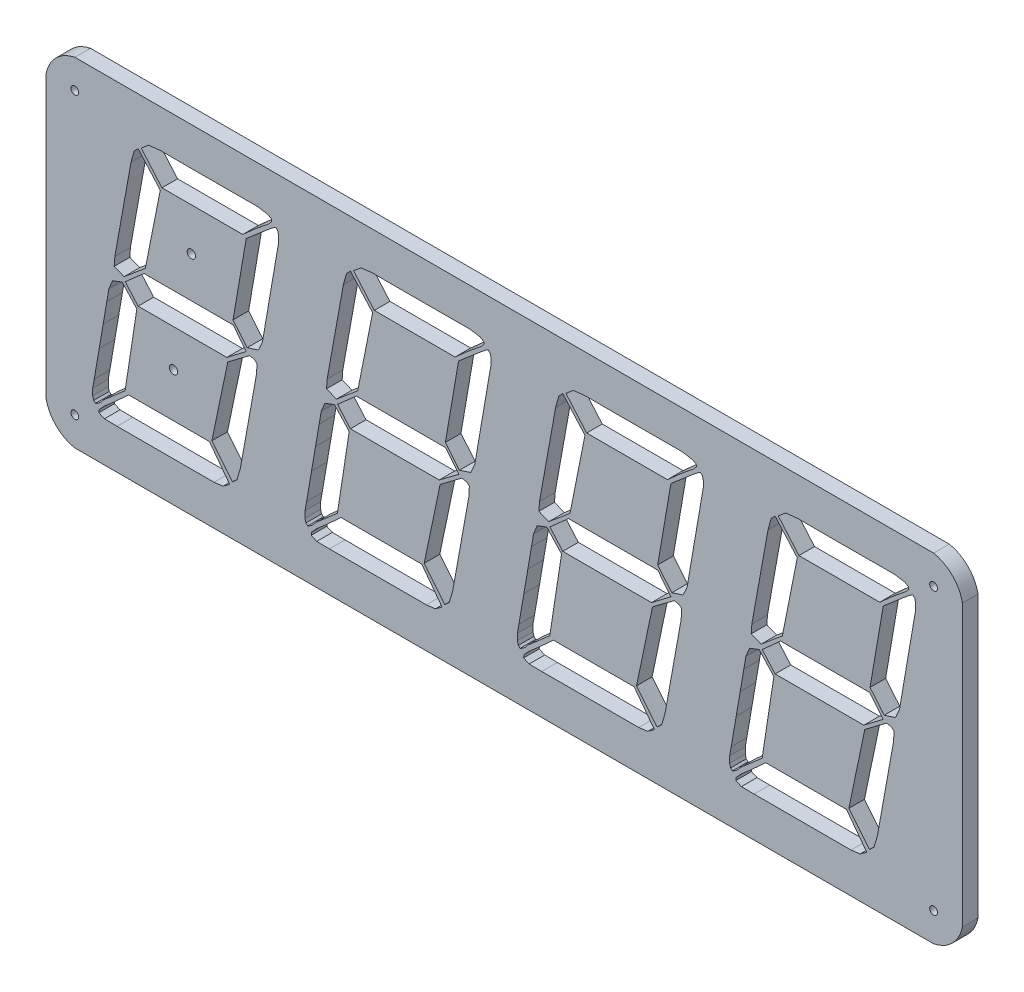
SolidWorks part; units mm, degrees
ref_plane "Alzado" through (0, 0, 0) normal (0, 0, 1) x (1, 0, 0)
ref_plane "Planta" through (0, 0, 0) normal (0, 1, 0) x (1, 0, 0)
ref_plane "Vista lateral" through (0, 0, 0) normal (1, 0, 0) x (0, 0, -1)
sketch "Model" plane through (0, 0, 0) normal (0, 0, 1) x (1, 0, 0)
  line L0 (-140.4707, 55.6745) -> (-140.4707, -52.2047)
  line L1 (-129.4104, 66.7349) -> (200.5896, 66.7349)
  line L2 (211.65, 55.6745) -> (211.65, -52.2047)
  line L3 (200.5896, -63.2651) -> (-129.4104, -63.2651)
  line L4 (-64.8849, 40.039) -> (-95.9228, 40.039)
  line L5 (-95.9228, 40.039) -> (-103.8826, 49.2647)
  line L6 (-110.033, 1.7349) -> (-102.8149, 8.0717)
  line L7 (-102.8149, 8.0717) -> (-68.5337, 8.0717)
  line L8 (-68.5337, 8.0717) -> (-63.5407, 1.7349)
  line L9 (-63.5407, 1.7349) -> (-70.9928, -3.9318)
  line L10 (-70.9928, -3.9318) -> (-105.0878, -3.9318)
  line L11 (-105.0878, -3.9318) -> (-110.033, 1.7349)
  line L12 (-108.7071, -35.2797) -> (-77.6692, -35.2797)
  line L13 (-77.6692, -35.2797) -> (-69.8725, -45.6529)
  line L14 (-55.6701, 46.1082) -> (-63.5407, 39.3548)
  line L15 (-63.5407, 39.3548) -> (-68.6061, 9.7375)
  line L16 (-68.6061, 9.7375) -> (-63.1847, 3.1943)
  line L17 (-105.072, 48.5077) -> (-96.5615, 38.9072)
  line L18 (-96.5615, 38.9072) -> (-102.297, 10.0462)
  line L19 (-102.297, 10.0462) -> (-110.4667, 3.1943)
  line L20 (-114.0199, 8.1319) -> (-107.8069, 42.6223)
  line L21 (-118.526, -41.8984) -> (-110.0791, -34.5639)
  line L22 (-110.0791, -34.5639) -> (-105.5639, -5.1304)
  line L23 (-105.5639, -5.1304) -> (-111.2067, 1.0264)
  line L24 (-68.8461, -44.3295) -> (-76.746, -34.5615)
  line L25 (-76.746, -34.5615) -> (-70.6289, -5.2553)
  line L26 (-70.6289, -5.2553) -> (-62.2742, 1.0143)
  line L27 (-59.5994, -3.9245) -> (-65.8121, -38.4144)
  line L28 (16.7066, 40.039) -> (-14.3313, 40.039)
  line L29 (-14.3313, 40.039) -> (-22.291, 49.2647)
  line L30 (-28.4415, 1.7349) -> (-21.2234, 8.0717)
  line L31 (-21.2234, 8.0717) -> (13.0578, 8.0717)
  line L32 (13.0578, 8.0717) -> (18.1744, 1.7349)
  line L33 (18.1744, 1.7349) -> (10.5987, -3.9318)
  line L34 (10.5987, -3.9318) -> (-23.4963, -3.9318)
  line L35 (-23.4963, -3.9318) -> (-28.4415, 1.7349)
  line L36 (-27.1156, -35.2797) -> (3.9223, -35.2797)
  line L37 (3.9223, -35.2797) -> (11.719, -45.6529)
  line L38 (25.9214, 46.1399) -> (18.0508, 39.3866)
  line L39 (18.0508, 39.3866) -> (12.9854, 9.7692)
  line L40 (12.9854, 9.7692) -> (18.4068, 3.226)
  line L41 (-23.4805, 48.5395) -> (-14.97, 38.9389)
  line L42 (-14.97, 38.9389) -> (-20.7055, 10.0779)
  line L43 (-20.7055, 10.0779) -> (-28.8752, 3.226)
  line L44 (-32.4284, 8.1637) -> (-26.2154, 42.6541)
  line L45 (-36.9345, -41.8666) -> (-28.4876, -34.5322)
  line L46 (-28.4876, -34.5322) -> (-23.9724, -5.0986)
  line L47 (-23.9724, -5.0986) -> (-29.6152, 1.0582)
  line L48 (12.7454, -44.2977) -> (4.8455, -34.5298)
  line L49 (4.8455, -34.5298) -> (10.9626, -5.2236)
  line L50 (10.9626, -5.2236) -> (19.3172, 1.0461)
  line L51 (21.9921, -3.8928) -> (15.7793, -38.3826)
  line L52 (98.2982, 40.039) -> (67.2602, 40.039)
  line L53 (67.2602, 40.039) -> (59.3004, 49.2647)
  line L54 (53.15, 1.7349) -> (60.2958, 8.0717)
  line L55 (60.2958, 8.0717) -> (94.577, 8.0717)
  line L56 (94.577, 8.0717) -> (99.6423, 1.7349)
  line L57 (99.6423, 1.7349) -> (92.1902, -3.9318)
  line L58 (92.1902, -3.9318) -> (58.0952, -3.9318)
  line L59 (58.0952, -3.9318) -> (53.15, 1.7349)
  line L60 (54.4759, -35.2797) -> (85.5138, -35.2797)
  line L61 (85.5138, -35.2797) -> (93.3104, -45.6529)
  line L62 (107.5129, 46.1717) -> (99.6423, 39.4183)
  line L63 (99.6423, 39.4183) -> (94.577, 9.801)
  line L64 (94.577, 9.801) -> (99.9983, 3.2578)
  line L65 (58.111, 48.5712) -> (66.6215, 38.9707)
  line L66 (66.6215, 38.9707) -> (60.886, 10.1097)
  line L67 (60.886, 10.1097) -> (52.7163, 3.2578)
  line L68 (49.1631, 8.1954) -> (55.376, 42.6858)
  line L69 (44.6571, -41.8349) -> (53.1039, -34.5004)
  line L70 (53.1039, -34.5004) -> (57.6191, -5.0669)
  line L71 (57.6191, -5.0669) -> (51.9763, 1.0899)
  line L72 (94.3369, -44.266) -> (86.437, -34.498)
  line L73 (86.437, -34.498) -> (92.5541, -5.1918)
  line L74 (92.5541, -5.1918) -> (100.9088, 1.0778)
  line L75 (103.5837, -3.861) -> (97.3708, -38.3509)
  line L76 (179.8897, 40.039) -> (148.8517, 40.039)
  line L77 (148.8517, 40.039) -> (140.8919, 49.2647)
  line L78 (134.7415, 1.7349) -> (141.8032, 8.0717)
  line L79 (141.8032, 8.0717) -> (176.0844, 8.0717)
  line L80 (176.0844, 8.0717) -> (181.2338, 1.7349)
  line L81 (181.2338, 1.7349) -> (173.7817, -3.9318)
  line L82 (173.7817, -3.9318) -> (139.6867, -3.9318)
  line L83 (139.6867, -3.9318) -> (134.7415, 1.7349)
  line L84 (136.0674, -35.2797) -> (167.1053, -35.2797)
  line L85 (167.1053, -35.2797) -> (174.902, -45.6529)
  line L86 (189.1044, 46.2034) -> (181.2338, 39.4501)
  line L87 (181.2338, 39.4501) -> (176.1685, 9.8327)
  line L88 (176.1685, 9.8327) -> (181.5897, 3.2895)
  line L89 (139.7025, 48.603) -> (148.213, 39.0024)
  line L90 (148.213, 39.0024) -> (142.4775, 10.1414)
  line L91 (142.4775, 10.1414) -> (134.3077, 3.2895)
  line L92 (130.7546, 8.2272) -> (136.9675, 42.7176)
  line L93 (126.2486, -41.8031) -> (134.6954, -34.4687)
  line L94 (134.6954, -34.4687) -> (139.2106, -5.0351)
  line L95 (139.2106, -5.0351) -> (133.5678, 1.1217)
  line L96 (175.9284, -44.2342) -> (168.0285, -34.4663)
  line L97 (168.0285, -34.4663) -> (174.1456, -5.1601)
  line L98 (174.1456, -5.1601) -> (182.5002, 1.1096)
  line L99 (185.1752, -3.8293) -> (178.9622, -38.3191)
  line L100 (-103.8826, 49.2647) -> (-101.0239, 51.6713)
  line L101 (-101.0239, 51.6713) -> (-96.2843, 52.1767)
  line L102 (-96.2843, 52.1767) -> (-90.7066, 52.1278)
  line L103 (-90.7066, 52.1278) -> (-81.4034, 52.1176)
  line L104 (-81.4034, 52.1176) -> (-71.4803, 52.1367)
  line L105 (-71.4803, 52.1367) -> (-59.2572, 52.1798)
  line L106 (-59.2572, 52.1798) -> (-55.2527, 51.5322)
  line L107 (-55.2527, 51.5322) -> (-53.814, 50.6949)
  line L108 (-53.814, 50.6949) -> (-53.7246, 49.8681)
  line L109 (-53.7246, 49.8681) -> (-54.9471, 48.5077)
  line L110 (-54.9471, 48.5077) -> (-60.0244, 44.3669)
  line L111 (-60.0244, 44.3669) -> (-64.8849, 40.039)
  line L112 (-69.8725, -45.6529) -> (-72.4165, -47.4989)
  line L113 (-72.4165, -47.4989) -> (-75.901, -47.9421)
  line L114 (-75.901, -47.9421) -> (-113.1682, -47.9421)
  line L115 (-113.1682, -47.9421) -> (-118.0367, -47.8925)
  line L116 (-118.0367, -47.8925) -> (-120.137, -46.9128)
  line L117 (-120.137, -46.9128) -> (-119.9993, -45.7428)
  line L118 (-119.9993, -45.7428) -> (-117.9018, -43.5397)
  line L119 (-117.9018, -43.5397) -> (-113.8983, -40.0461)
  line L120 (-113.8983, -40.0461) -> (-108.7071, -35.2797)
  line L121 (-52.1424, 48.6739) -> (-52.2526, 48.6647)
  line L122 (-52.2526, 48.6647) -> (-52.3754, 48.6202)
  line L123 (-52.3754, 48.6202) -> (-52.6739, 48.4594)
  line L124 (-52.6739, 48.4594) -> (-53.46, 47.9126)
  line L125 (-53.46, 47.9126) -> (-55.6701, 46.1082)
  line L126 (-63.1847, 3.1943) -> (-58.8538, 4.5867)
  line L127 (-58.8538, 4.5867) -> (-57.2981, 8.0082)
  line L128 (-57.2981, 8.0082) -> (-56.5159, 12.6185)
  line L129 (-56.5159, 12.6185) -> (-55.1164, 20.7958)
  line L130 (-55.1164, 20.7958) -> (-53.5837, 29.7233)
  line L131 (-53.5837, 29.7233) -> (-51.6699, 40.853)
  line L132 (-51.6699, 40.853) -> (-51.0729, 44.2025)
  line L133 (-51.0729, 44.2025) -> (-51.0882, 46.6565)
  line L134 (-51.0882, 46.6565) -> (-51.4412, 48.0489)
  line L135 (-51.4412, 48.0489) -> (-52.1424, 48.6739)
  line L136 (-107.8069, 42.6223) -> (-106.6025, 46.9642)
  line L137 (-106.6025, 46.9642) -> (-105.072, 48.5077)
  line L138 (-110.4667, 3.1943) -> (-114.2667, 4.7427)
  line L139 (-114.2667, 4.7427) -> (-114.0199, 8.1319)
  line L140 (-111.2067, 1.0264) -> (-114.9136, -0.3758)
  line L141 (-114.9136, -0.3758) -> (-116.3199, -3.7996)
  line L142 (-116.3199, -3.7996) -> (-117.102, -8.41)
  line L143 (-117.102, -8.41) -> (-118.501, -16.5876)
  line L144 (-118.501, -16.5876) -> (-120.0332, -25.5155)
  line L145 (-120.0332, -25.5155) -> (-121.9463, -36.6456)
  line L146 (-121.9463, -36.6456) -> (-122.5453, -39.9939)
  line L147 (-122.5453, -39.9939) -> (-122.5304, -42.4479)
  line L148 (-122.5304, -42.4479) -> (-122.1765, -43.8408)
  line L149 (-122.1765, -43.8408) -> (-121.4756, -44.4653)
  line L150 (-65.8121, -38.4144) -> (-67.1101, -42.7658)
  line L151 (-67.1101, -42.7658) -> (-68.8461, -44.3295)
  line L152 (-62.2742, 1.0143) -> (-60.4446, 0.7056)
  line L153 (-60.4446, 0.7056) -> (-59.3889, -0.2204)
  line L154 (-59.3889, -0.2204) -> (-59.5994, -3.9245)
  line L155 (-22.291, 49.2647) -> (-19.4324, 51.6713)
  line L156 (-19.4324, 51.6713) -> (-14.6928, 52.1767)
  line L157 (-14.6928, 52.1767) -> (-9.1151, 52.1278)
  line L158 (-9.1151, 52.1278) -> (0.1881, 52.1176)
  line L159 (0.1881, 52.1176) -> (10.1112, 52.1367)
  line L160 (10.1112, 52.1367) -> (22.3342, 52.1798)
  line L161 (22.3342, 52.1798) -> (26.3388, 51.5322)
  line L162 (26.3388, 51.5322) -> (27.7775, 50.6949)
  line L163 (27.7775, 50.6949) -> (27.8669, 49.8681)
  line L164 (27.8669, 49.8681) -> (26.6444, 48.5077)
  line L165 (26.6444, 48.5077) -> (21.5671, 44.3669)
  line L166 (21.5671, 44.3669) -> (16.7066, 40.039)
  line L167 (11.719, -45.6529) -> (9.175, -47.4989)
  line L168 (9.175, -47.4989) -> (5.6904, -47.9421)
  line L169 (5.6904, -47.9421) -> (-31.5768, -47.9421)
  line L170 (-31.5768, -47.9421) -> (-36.4452, -47.8925)
  line L171 (-36.4452, -47.8925) -> (-38.5455, -46.9128)
  line L172 (-38.5455, -46.9128) -> (-38.4078, -45.7428)
  line L173 (-38.4078, -45.7428) -> (-36.3103, -43.5397)
  line L174 (-36.3103, -43.5397) -> (-32.3068, -40.0461)
  line L175 (-32.3068, -40.0461) -> (-27.1156, -35.2797)
  line L176 (29.4491, 48.7056) -> (29.3389, 48.6964)
  line L177 (29.3389, 48.6964) -> (29.2161, 48.652)
  line L178 (29.2161, 48.652) -> (28.9176, 48.4912)
  line L179 (28.9176, 48.4912) -> (28.1315, 47.9444)
  line L180 (28.1315, 47.9444) -> (25.9214, 46.1399)
  line L181 (18.4068, 3.226) -> (22.7377, 4.6185)
  line L182 (22.7377, 4.6185) -> (24.2934, 8.0399)
  line L183 (24.2934, 8.0399) -> (25.0756, 12.6502)
  line L184 (25.0756, 12.6502) -> (26.4751, 20.8276)
  line L185 (26.4751, 20.8276) -> (28.0078, 29.7551)
  line L186 (28.0078, 29.7551) -> (29.9216, 40.8848)
  line L187 (29.9216, 40.8848) -> (30.5186, 44.2343)
  line L188 (30.5186, 44.2343) -> (30.5033, 46.6883)
  line L189 (30.5033, 46.6883) -> (30.1503, 48.0806)
  line L190 (30.1503, 48.0806) -> (29.4491, 48.7056)
  line L191 (-26.2154, 42.6541) -> (-25.011, 46.9959)
  line L192 (-25.011, 46.9959) -> (-23.4805, 48.5395)
  line L193 (-28.8752, 3.226) -> (-32.6752, 4.7745)
  line L194 (-32.6752, 4.7745) -> (-32.4284, 8.1637)
  line L195 (-29.6152, 1.0582) -> (-33.3221, -0.3441)
  line L196 (-33.3221, -0.3441) -> (-34.7284, -3.7678)
  line L197 (-34.7284, -3.7678) -> (-35.5104, -8.3782)
  line L198 (-35.5104, -8.3782) -> (-36.9095, -16.5559)
  line L199 (-36.9095, -16.5559) -> (-38.4417, -25.4838)
  line L200 (-38.4417, -25.4838) -> (-40.3548, -36.6139)
  line L201 (-40.3548, -36.6139) -> (-40.9538, -39.9621)
  line L202 (-40.9538, -39.9621) -> (-40.9389, -42.4162)
  line L203 (-40.9389, -42.4162) -> (-40.585, -43.809)
  line L204 (-40.585, -43.809) -> (-39.8841, -44.4336)
  line L205 (15.7793, -38.3826) -> (14.4814, -42.7341)
  line L206 (14.4814, -42.7341) -> (12.7454, -44.2977)
  line L207 (19.3172, 1.0461) -> (21.1469, 0.7374)
  line L208 (21.1469, 0.7374) -> (22.2026, -0.1886)
  line L209 (22.2026, -0.1886) -> (21.9921, -3.8928)
  line L210 (59.3004, 49.2647) -> (62.1591, 51.6713)
  line L211 (62.1591, 51.6713) -> (66.8987, 52.1767)
  line L212 (66.8987, 52.1767) -> (72.4764, 52.1278)
  line L213 (72.4764, 52.1278) -> (81.7796, 52.1176)
  line L214 (81.7796, 52.1176) -> (91.7027, 52.1367)
  line L215 (91.7027, 52.1367) -> (103.9257, 52.1798)
  line L216 (103.9257, 52.1798) -> (107.9303, 51.5322)
  line L217 (107.9303, 51.5322) -> (109.369, 50.6949)
  line L218 (109.369, 50.6949) -> (109.4584, 49.8681)
  line L219 (109.4584, 49.8681) -> (108.2359, 48.5077)
  line L220 (108.2359, 48.5077) -> (103.1586, 44.3669)
  line L221 (103.1586, 44.3669) -> (98.2982, 40.039)
  line L222 (93.3104, -45.6529) -> (90.7665, -47.4989)
  line L223 (90.7665, -47.4989) -> (87.2819, -47.9421)
  line L224 (87.2819, -47.9421) -> (50.0147, -47.9421)
  line L225 (50.0147, -47.9421) -> (45.1463, -47.8925)
  line L226 (45.1463, -47.8925) -> (43.046, -46.9128)
  line L227 (43.046, -46.9128) -> (43.1837, -45.7428)
  line L228 (43.1837, -45.7428) -> (45.2812, -43.5397)
  line L229 (45.2812, -43.5397) -> (49.2847, -40.0461)
  line L230 (49.2847, -40.0461) -> (54.4759, -35.2797)
  line L231 (111.0406, 48.7374) -> (110.9304, 48.7282)
  line L232 (110.9304, 48.7282) -> (110.8076, 48.6837)
  line L233 (110.8076, 48.6837) -> (110.5091, 48.5229)
  line L234 (110.5091, 48.5229) -> (109.723, 47.9761)
  line L235 (109.723, 47.9761) -> (107.5129, 46.1717)
  line L236 (99.9983, 3.2578) -> (104.3292, 4.6502)
  line L237 (104.3292, 4.6502) -> (105.8849, 8.0717)
  line L238 (105.8849, 8.0717) -> (106.6671, 12.682)
  line L239 (106.6671, 12.682) -> (108.0666, 20.8593)
  line L240 (108.0666, 20.8593) -> (109.5993, 29.7869)
  line L241 (109.5993, 29.7869) -> (111.5131, 40.9165)
  line L242 (111.5131, 40.9165) -> (112.1101, 44.266)
  line L243 (112.1101, 44.266) -> (112.0948, 46.72)
  line L244 (112.0948, 46.72) -> (111.7418, 48.1124)
  line L245 (111.7418, 48.1124) -> (111.0406, 48.7374)
  line L246 (55.376, 42.6858) -> (56.5805, 47.0277)
  line L247 (56.5805, 47.0277) -> (58.111, 48.5712)
  line L248 (52.7163, 3.2578) -> (48.9163, 4.8062)
  line L249 (48.9163, 4.8062) -> (49.1631, 8.1954)
  line L250 (51.9763, 1.0899) -> (48.2694, -0.3123)
  line L251 (48.2694, -0.3123) -> (46.8631, -3.7361)
  line L252 (46.8631, -3.7361) -> (46.0811, -8.3465)
  line L253 (46.0811, -8.3465) -> (44.682, -16.5241)
  line L254 (44.682, -16.5241) -> (43.1498, -25.452)
  line L255 (43.1498, -25.452) -> (41.2367, -36.5821)
  line L256 (41.2367, -36.5821) -> (40.6377, -39.9304)
  line L257 (40.6377, -39.9304) -> (40.6526, -42.3844)
  line L258 (40.6526, -42.3844) -> (41.0065, -43.7773)
  line L259 (41.0065, -43.7773) -> (41.7074, -44.4018)
  line L260 (97.3708, -38.3509) -> (96.073, -42.7023)
  line L261 (96.073, -42.7023) -> (94.3369, -44.266)
  line L262 (100.9088, 1.0778) -> (102.7384, 0.7691)
  line L263 (102.7384, 0.7691) -> (103.7941, -0.1569)
  line L264 (103.7941, -0.1569) -> (103.5837, -3.861)
  line L265 (140.8919, 49.2647) -> (143.7506, 51.6713)
  line L266 (143.7506, 51.6713) -> (148.4902, 52.1767)
  line L267 (148.4902, 52.1767) -> (154.0679, 52.1278)
  line L268 (154.0679, 52.1278) -> (163.3711, 52.1176)
  line L269 (163.3711, 52.1176) -> (173.2942, 52.1367)
  line L270 (173.2942, 52.1367) -> (185.5172, 52.1798)
  line L271 (185.5172, 52.1798) -> (189.5219, 51.5322)
  line L272 (189.5219, 51.5322) -> (190.9605, 50.6949)
  line L273 (190.9605, 50.6949) -> (191.0499, 49.8681)
  line L274 (191.0499, 49.8681) -> (189.8273, 48.5077)
  line L275 (189.8273, 48.5077) -> (184.7501, 44.3669)
  line L276 (184.7501, 44.3669) -> (179.8897, 40.039)
  line L277 (174.902, -45.6529) -> (172.358, -47.4989)
  line L278 (172.358, -47.4989) -> (168.8734, -47.9421)
  line L279 (168.8734, -47.9421) -> (131.6062, -47.9421)
  line L280 (131.6062, -47.9421) -> (126.7378, -47.8925)
  line L281 (126.7378, -47.8925) -> (124.6375, -46.9128)
  line L282 (124.6375, -46.9128) -> (124.7752, -45.7428)
  line L283 (124.7752, -45.7428) -> (126.8727, -43.5397)
  line L284 (126.8727, -43.5397) -> (130.8762, -40.0461)
  line L285 (130.8762, -40.0461) -> (136.0674, -35.2797)
  line L286 (192.6321, 48.7691) -> (192.522, 48.7599)
  line L287 (192.522, 48.7599) -> (192.3992, 48.7155)
  line L288 (192.3992, 48.7155) -> (192.1006, 48.5547)
  line L289 (192.1006, 48.5547) -> (191.3145, 48.0079)
  line L290 (191.3145, 48.0079) -> (189.1044, 46.2034)
  line L291 (181.5897, 3.2895) -> (185.9207, 4.682)
  line L292 (185.9207, 4.682) -> (187.4764, 8.1034)
  line L293 (187.4764, 8.1034) -> (188.2586, 12.7137)
  line L294 (188.2586, 12.7137) -> (189.6581, 20.8911)
  line L295 (189.6581, 20.8911) -> (191.1908, 29.8186)
  line L296 (191.1908, 29.8186) -> (193.1046, 40.9483)
  line L297 (193.1046, 40.9483) -> (193.7016, 44.2978)
  line L298 (193.7016, 44.2978) -> (193.6862, 46.7518)
  line L299 (193.6862, 46.7518) -> (193.3333, 48.1441)
  line L300 (193.3333, 48.1441) -> (192.6321, 48.7691)
  line L301 (136.9675, 42.7176) -> (138.172, 47.0594)
  line L302 (138.172, 47.0594) -> (139.7025, 48.603)
  line L303 (134.3077, 3.2895) -> (130.5078, 4.838)
  line L304 (130.5078, 4.838) -> (130.7546, 8.2272)
  line L305 (133.5678, 1.1217) -> (129.8609, -0.2806)
  line L306 (129.8609, -0.2806) -> (128.4546, -3.7043)
  line L307 (128.4546, -3.7043) -> (127.6726, -8.3147)
  line L308 (127.6726, -8.3147) -> (126.2735, -16.4924)
  line L309 (126.2735, -16.4924) -> (124.7413, -25.4203)
  line L310 (124.7413, -25.4203) -> (122.8282, -36.5504)
  line L311 (122.8282, -36.5504) -> (122.2292, -39.8986)
  line L312 (122.2292, -39.8986) -> (122.2441, -42.3527)
  line L313 (122.2441, -42.3527) -> (122.598, -43.7455)
  line L314 (122.598, -43.7455) -> (123.2989, -44.3701)
  line L315 (178.9622, -38.3191) -> (177.6645, -42.6706)
  line L316 (177.6645, -42.6706) -> (175.9284, -44.2342)
  line L317 (182.5002, 1.1096) -> (184.3299, 0.8009)
  line L318 (184.3299, 0.8009) -> (185.3856, -0.1251)
  line L319 (185.3856, -0.1251) -> (185.1752, -3.8293)
  arc A0 (-129.4104, 66.7349) -> (-140.4707, 55.6745) centre (-126.7298, 52.9939) ccw
  arc A1 (211.65, 55.6745) -> (200.5896, 66.7349) centre (197.909, 52.9939) ccw
  arc A2 (-140.4707, -52.2047) -> (-129.4104, -63.2651) centre (-126.7298, -49.5241) ccw
  arc A3 (200.5896, -63.2651) -> (211.65, -52.2047) centre (197.909, -49.5241) ccw
  circle A4 centre (-129.4104, 55.6745) radius 1.5
  circle A5 centre (-129.4104, -52.2323) radius 1.5
  circle A6 centre (200.5896, -52.2047) radius 1.5
  circle A7 centre (200.5896, 55.6745) radius 1.5
  arc A8 (-121.4756, -44.4653) -> (-118.526, -41.8984) centre (-124.1963, -38.3607) ccw
  arc A9 (-39.8841, -44.4336) -> (-36.9345, -41.8666) centre (-42.6044, -38.3295) ccw
  arc A10 (41.7074, -44.4018) -> (44.6571, -41.8349) centre (38.9873, -38.2979) ccw
  arc A11 (123.2989, -44.3701) -> (126.2486, -41.8031) centre (120.5787, -38.2661) ccw
  circle A12 centre (-84.6214, 23.6743) radius 1.6
  circle A13 centre (-91.4444, -18.2527) radius 1.6
  point P344 (-140.4707, 1.7349)
  point P345 (35.5896, 66.7349)
extrude "Saliente-Extruir1" add sketch "Model" along normal blind 6
